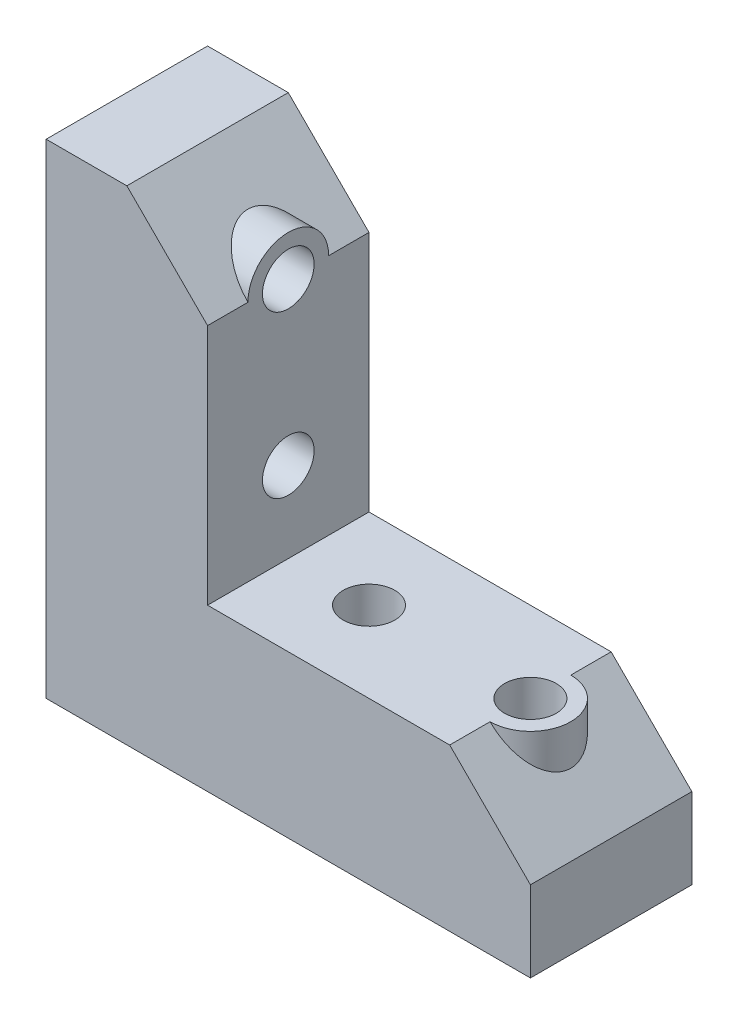
SolidWorks part; units mm, degrees
ref_plane "Ebene vorne" through (0, 0, 0) normal (0, 0, 1) x (1, 0, 0)
ref_plane "Ebene oben" through (0, 0, 0) normal (0, 1, 0) x (1, 0, 0)
ref_plane "Ebene rechts" through (0, 0, 0) normal (1, 0, 0) x (0, 0, -1)
sketch "Skizze1" plane through (0, 0, 0) normal (0, 0, 1) x (1, 0, 0)
  line L0 (0, 30) -> (10, 30)
  line L1 (0, 0) -> (0, 30)
  line L2 (10, 30) -> (10, 10)
  line L3 (10, 10) -> (30, 10)
  line L4 (30, 0) -> (0, 0)
  line L5 (30, 10) -> (30, 0)
extrude "Aufsatz-Linear austragen1" add sketch "Skizze1" along normal blind 10
chamfer "Fase1" distance 5 angle 45 2 edges at (10, 30, 5) (30, 10, 5)
sketch "Skizze2" plane through (0, 0, 0) normal (-1, 0, 0) x (0, 0, 1)
  circle A0 centre (5, 15) radius 1.6
  circle A1 centre (5, 25) radius 1.6
  dimension "D1" = 2
extrude "Schnitt-Linear austragen1" cut sketch "Skizze2" against normal blind 10
sketch "Skizze3" plane through (0, 0, 0) normal (-1, 0, 0) x (0, 0, 1)
  circle A0 centre (5, 25) radius 2.5
  circle A1 centre (5, 25) radius 1.6
extrude "Aufsatz-Linear austragen2" add sketch "Skizze3" against normal blind 10
sketch "Skizze4" plane through (0, 0, 0) normal (0, -1, 0) x (1, 0, 0)
  circle A0 centre (15, 5) radius 1.6
  circle A1 centre (25, 5) radius 1.6
  circle A2 centre (25, 5) radius 1.6
  circle A3 centre (25, 5) radius 2.5
sketch "Skizze5" plane through (0, 0, 0) normal (0, -1, 0) x (1, 0, 0)
  circle A0 centre (25, 5) radius 1.6
  circle A1 centre (25, 5) radius 2.5
extrude "Aufsatz-Linear austragen3" add sketch "Skizze5" against normal blind 10
extrude "Schnitt-Linear austragen3" cut sketch "Skizze4" against normal blind 10 contours A0 | A1
